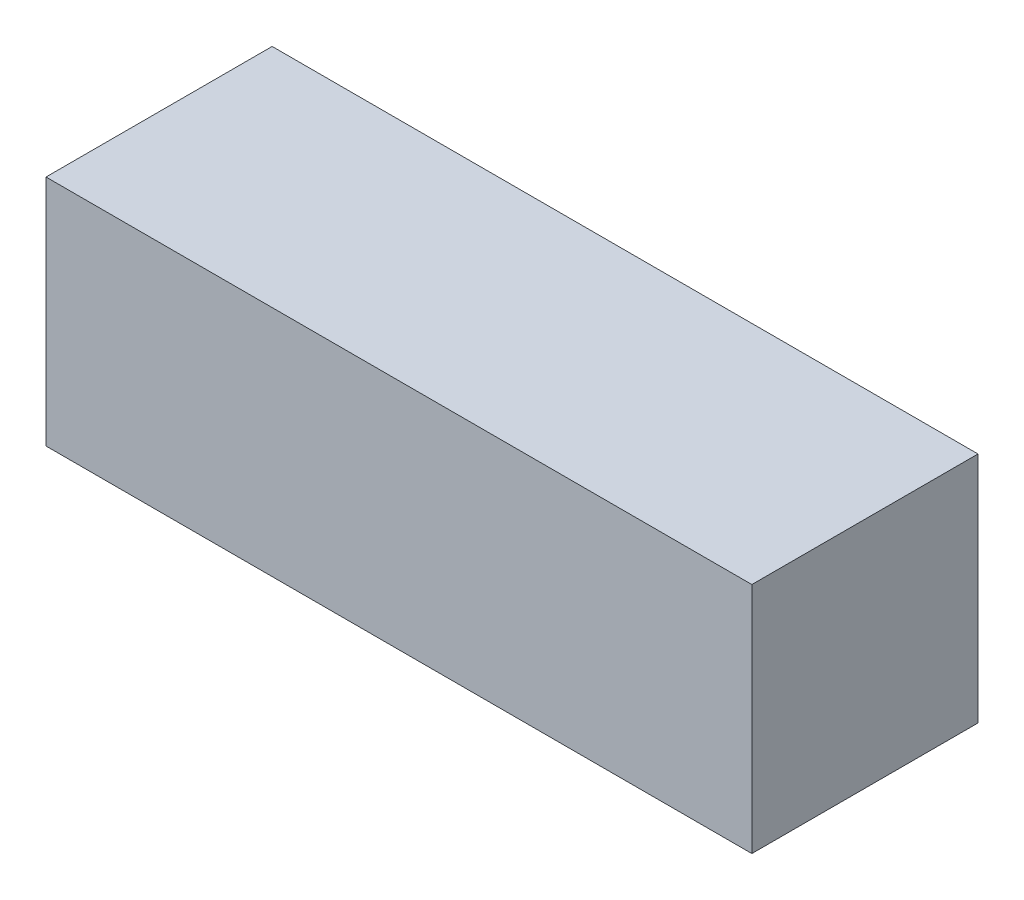
SolidWorks part; units mm, degrees
ref_plane "Front Plane" through (0, 0, 0) normal (0, 0, 1) x (1, 0, 0)
ref_plane "Top Plane" through (0, 0, 0) normal (0, 1, 0) x (1, 0, 0)
ref_plane "Right Plane" through (0, 0, 0) normal (1, 0, 0) x (0, 0, -1)
sketch "Sketch1" plane through (0, 0, 0) normal (0, 1, 0) x (1, 0, 0)
  line L1 (0, 0) -> (103, 0)
  line L2 (0, 0) -> (0, 33)
  line L3 (0, 33) -> (103, 33)
  line L4 (103, 0) -> (103, 33)
  dimension "D1" = 33
  dimension "D2" = 103
extrude "Boss-Extrude1" add sketch "Sketch1" along normal blind 34
